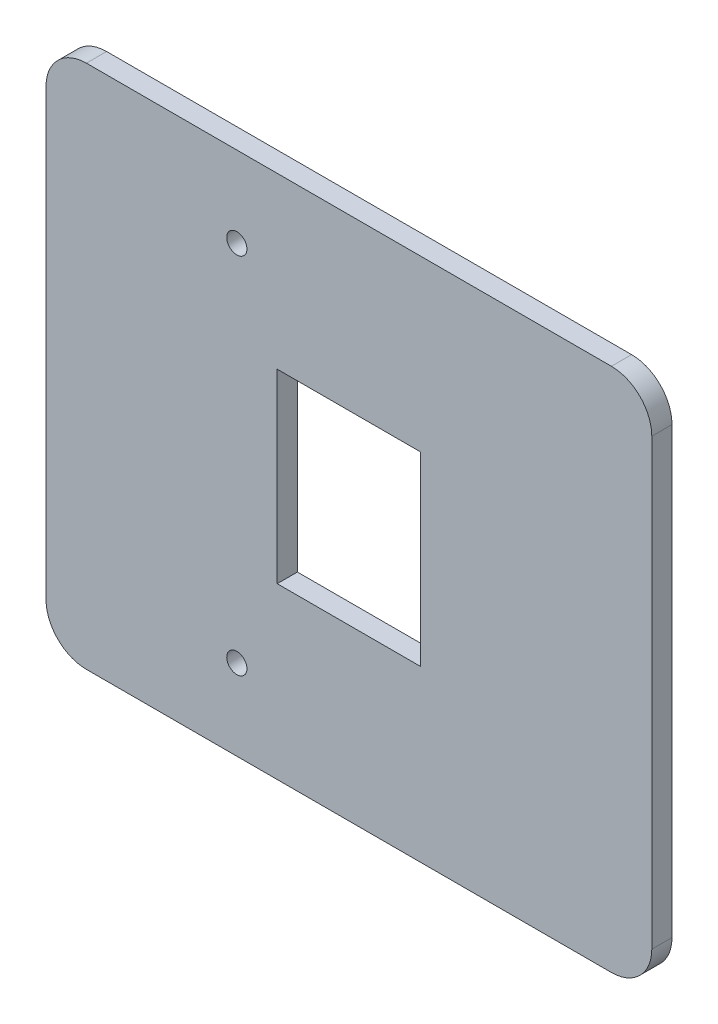
SolidWorks part; units mm, degrees
ref_plane "前视基准面" through (0, 0, 0) normal (0, 0, 1) x (1, 0, 0)
ref_plane "上视基准面" through (0, 0, 0) normal (0, 1, 0) x (1, 0, 0)
ref_plane "右视基准面" through (0, 0, 0) normal (1, 0, 0) x (0, 0, -1)
sketch "草图3" plane through (0, 0, 0) normal (0, 0, 1) x (1, 0, 0)
  line L1 (-75, 65) -> (75, 65)
  line L2 (-75, 65) -> (-75, -65)
  line L3 (-75, -65) -> (75, -65)
  line L4 (75, 65) -> (75, -65)
  line L5 (0, -65) -> (0, 65) construction
  line L6 (-75, 0) -> (75, 0) construction
  point P0 (0, 0)
  dimension "D1" = 130
  dimension "D2" = 150
extrude "凸台-拉伸1" add sketch "草图3" along normal blind 5
sketch "草图4" plane through (0, 0, 5) normal (0, 0, 1) x (1, 0, 0)
  line L0 (-17.75, -8) -> (-30, -8)
  line L1 (-17.75, 23) -> (17.75, 23)
  line L2 (-17.75, 23) -> (-17.75, -23)
  line L3 (-17.75, -23) -> (17.75, -23)
  line L4 (17.75, 23) -> (17.75, -23)
  line L5 (0, -23) -> (0, 23) construction
  line L6 (-17.75, 0) -> (17.75, 0) construction
  line L7 (-30, -8) -> (-30, -23)
  line L8 (-30, -23) -> (-17.75, -23)
  line L9 (30, -23) -> (17.75, -23)
  line L10 (30, -8) -> (30, -23)
  line L11 (17.75, -8) -> (30, -8)
  circle A0 centre (-27.75, 45) radius 2.5
  circle A1 centre (-27.75, -45) radius 2.5
  point P0 (0, 0)
  point P14 (30, -15.5)
  point P15 (-23.4335, -45)
  dimension "D3" = 90
  dimension "D1" = 46
  dimension "D2" = 35.5
  dimension "D4" = 60
  dimension "D5" = 15
  dimension "D6" = 27.75
extrude "切除-拉伸1" cut sketch "草图4" against normal blind 10 contours L4 L1 L2 L3 | A1 | A0
fillet "圆角1" radius 10 4 edges at (-75, -65, 2.5) (75, -65, 2.5) (75, 65, 2.5) (-75, 65, 2.5)
sketch "草图5" plane through (0, 0, 5) normal (0, 0, 1) x (1, 0, 0)
  line L0 (0, 60) -> (0, -60) construction
  line L1 (-71.731, 0) -> (70.6604, 0) construction
  line L2 (-54.7503, 54.7503) -> (52.9749, -52.9749) construction
  line L3 (54.7503, 54.7503) -> (-52.9749, -52.9749) construction
  line L4 (54.7503, -54.7503) -> (-52.9749, 52.9749) construction
  line L5 (-54.7503, -54.7503) -> (52.9749, 52.9749) construction
  circle A0 centre (0, 0) radius 60
  circle A1 centre (0, 0) radius 50
  circle A2 centre (0, 0) radius 40
  point P19 (0, 0)
  dimension "D1" = 45
  dimension "D2" = 4
